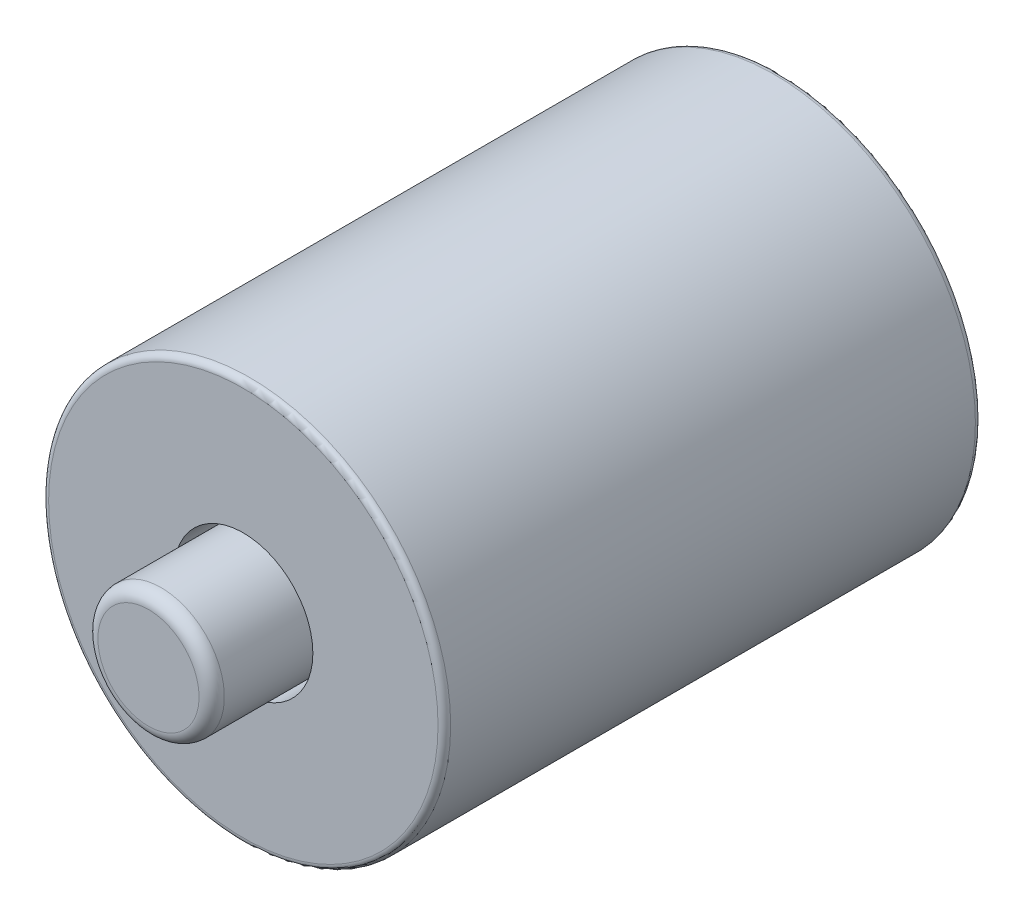
SolidWorks part; units mm, degrees
ref_plane "Front Plane" through (0, 0, 0) normal (0, 0, 1) x (1, 0, 0)
ref_plane "Top Plane" through (0, 0, 0) normal (0, 1, 0) x (1, 0, 0)
ref_plane "Right Plane" through (0, 0, 0) normal (1, 0, 0) x (0, 0, -1)
sketch "Sketch1" plane through (0, 0, 0) normal (0, 0, 1) x (1, 0, 0)
  circle A0 centre (0, 0) radius 3.18
extrude "Boss-Extrude1" add sketch "Sketch1" along normal blind 8.5 contours A0
sketch "Sketch2" plane through (0, 0, 8.5) normal (0, 0, 1) x (1, 0, 0)
  circle A0 centre (0, 0) radius 1.1
extrude "Cut-Extrude1" cut sketch "Sketch2" against normal through all both and the other way through all contours A0
sketch "Sketch3" plane through (0, 0, 0) normal (0, 0, -1) x (-1, 0, 0)
  circle A0 centre (0, 0) radius 1
extrude "Boss-Extrude2" add sketch "Sketch3" against normal blind 10 separate body contours A0
fillet "Fillet1" radius 0.2 1 edges at (-1, 0, 10)
fillet "Fillet2" radius 0.1 1 edges at (3.18, 0, 8.5)
fillet "Fillet3" radius 0.1 1 edges at (3.18, 0, 0)
